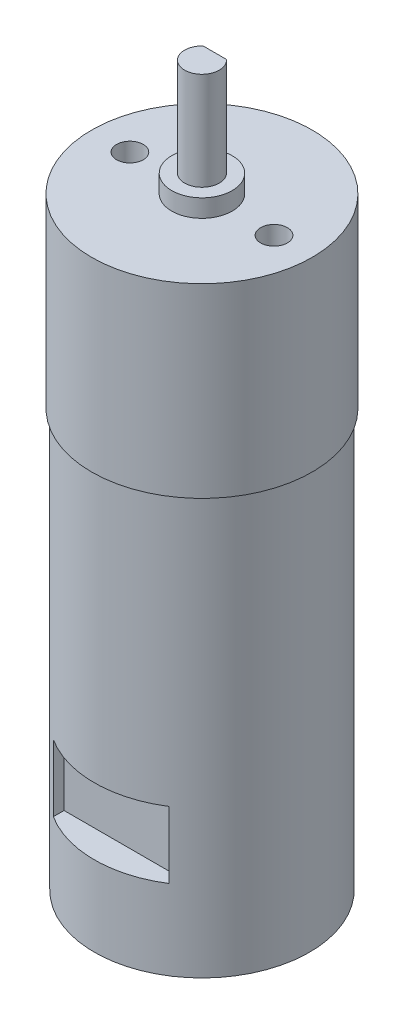
SolidWorks part; units mm, degrees
material "Plain Carbon Steel"
ref_plane "Front Plane" through (0, 0, 0) normal (0, 0, 1) x (1, 0, 0)
ref_plane "Top Plane" through (0, 0, 0) normal (0, 1, 0) x (1, 0, 0)
ref_plane "Right Plane" through (0, 0, 0) normal (1, 0, 0) x (0, 0, -1)
sketch "Sketch1" plane through (0, 0, 0) normal (0, 1, 0) x (1, 0, 0)
  circle A0 centre (0, 0) radius 12.4
  dimension "D1" = 24.8
extrude "Boss-Extrude1" add sketch "Sketch1" along normal blind 20.9
sketch "Sketch4" plane through (0, 20.9, 0) normal (0, 1, 0) x (1, 0, 0)
  circle A0 centre (0, 0) radius 3.4
  dimension "D1" = 6.8
extrude "Boss-Extrude3" add sketch "Sketch4" along normal blind 2
sketch "Sketch6" plane through (0, 22.9, 0) normal (0, 1, 0) x (1, 0, 0)
  circle A0 centre (0, 0) radius 1.95
  dimension "D1" = 3.9
extrude "Boss-Extrude4" add sketch "Sketch6" along normal blind 11
sketch "Sketch7" plane through (0, 33.9, 0) normal (0, 1, 0) x (1, 0, 0)
  line L0 (0, 1.95) -> (0, 1.45) construction
  line L1 (0, 1.45) -> (-1.8405, 1.45)
  line L2 (-1.8405, 1.45) -> (-1.8405, 3.3293)
  line L3 (-1.8405, 3.3293) -> (1.8449, 3.3293)
  line L4 (1.8449, 3.3293) -> (1.8449, 1.45)
  line L5 (1.8449, 1.45) -> (0, 1.45)
  circle A0 centre (0, 0) radius 1.95 construction
  circle A1 centre (0, 0) radius 1.95 construction
  dimension "D1" = 0.5
extrude "Cut-Extrude1" cut sketch "Sketch7" against normal blind 10
sketch "Sketch8" plane through (0, 0, 0) normal (0, -1, 0) x (1, 0, 0)
  circle A0 centre (0, 0) radius 12.1
extrude "Boss-Extrude5" add sketch "Sketch8" along normal blind 46.9
sketch "Sketch9" plane through (0, 20.9, 0) normal (0, 1, 0) x (1, 0, 0)
  line L0 (0, 0) -> (0, -8.3178) construction
  circle A0 centre (-8.1, 0) radius 1.5
  circle A1 centre (0, 0) radius 12.4 construction
  circle A3 centre (8.1, 0) radius 1.5
  dimension "D1" = 8.1
  dimension "D2" = 3
extrude "Cut-Extrude2" cut sketch "Sketch9" against normal blind 5
ref_plane "Plane2" through (0, 0, 13) normal (0, 0, 1) x (1, 0, 0)
sketch "Sketch10" plane through (0, 0, 13) normal (0, 0, 1) x (1, 0, 0)
  line L0 (-12.1, -46.9) -> (12.1, -46.9) construction
  line L1 (-6.5, -30.4) -> (6.5, -30.4)
  line L2 (-6.5, -30.4) -> (-6.5, -37.9)
  line L3 (-6.5, -37.9) -> (6.5, -37.9)
  line L4 (6.5, -30.4) -> (6.5, -37.9)
  dimension "D1" = 9
  dimension "D2" = 13
  dimension "D3" = 7.5
extrude "Cut-Extrude3" cut sketch "Sketch10" against normal blind 4
